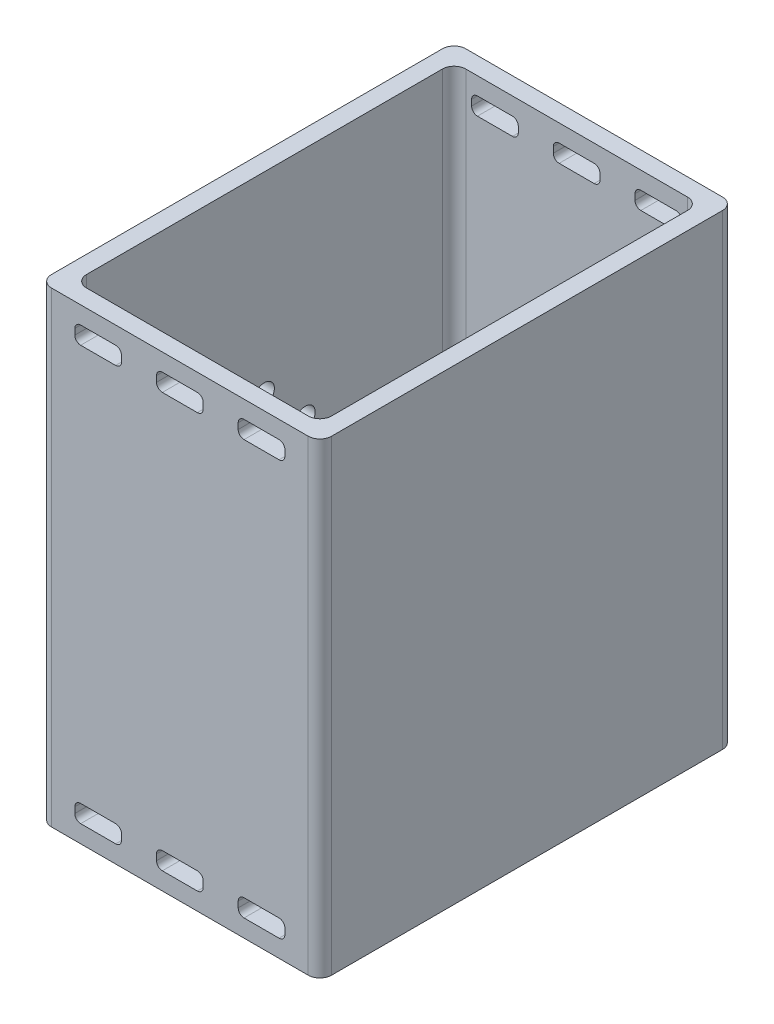
SolidWorks part; units mm, degrees
ref_plane "Front Plane" through (0, 0, 0) normal (0, 0, 1) x (1, 0, 0)
ref_plane "Top Plane" through (0, 0, 0) normal (0, 1, 0) x (1, 0, 0)
ref_plane "Right Plane" through (0, 0, 0) normal (1, 0, 0) x (0, 0, -1)
sketch "Sketch1" plane through (0, 0, 0) normal (0, 1, 0) x (1, 0, 0)
  line L0 (-24, 35.5) -> (24, 35.5)
  line L1 (-21, -32.5) -> (21, -32.5)
  line L2 (-21, -32.5) -> (-21, 32.5)
  line L3 (-21, 32.5) -> (21, 32.5)
  line L4 (21, -32.5) -> (21, 32.5)
  line L5 (-21, -32.5) -> (21, 32.5) construction
  line L6 (-21, 32.5) -> (21, -32.5) construction
  line L7 (24, -35.5) -> (24, 35.5)
  line L8 (-24, -35.5) -> (24, -35.5)
  line L9 (-24, -35.5) -> (-24, 35.5)
  point P0 (0, 0)
  dimension "D1" = 65
  dimension "D2" = 42
  dimension "D3" = 3
extrude "Boss-Extrude1" add sketch "Sketch1" along normal blind 80
sketch "Sketch2" plane through (-21, 0, 0) normal (1, 0, 0) x (0, 0, -1)
  line L0 (0, 0) -> (0, 80) construction
  line L1 (-35.5, 80) -> (35.5, 80) construction
  line L2 (-35.5, 40) -> (35.5, 40) construction
  line L3 (-35.5, 80) -> (-35.5, 0) construction
  line L4 (35.5, 80) -> (35.5, 0) construction
  circle A0 centre (0, 40) radius 1.5
  circle A1 centre (0, 40) radius 7
  circle A2 centre (-7, 40) radius 1.5
  circle A3 centre (0, 47) radius 1.5
  circle A4 centre (7, 40) radius 1.5
  circle A5 centre (0, 33) radius 1.5
  dimension "D1" = 3
  dimension "D2" = 14
  dimension "D3" = 3
  dimension "D4" = 3
  dimension "D5" = 3
  dimension "D6" = 3
hole_wizard "M3 Clearance Hole1" positions "Sketch3" profile "Sketch4" hole size "M3" standard "ISO"
sketch "Sketch3" plane through (-21, 0, 0) normal (1, 0, 0) x (0, 0, -1)
  point P0 (0, 40)
  point P3 (0, 47)
  point P6 (7, 40)
  point P9 (0, 33)
  point P12 (-7, 40)
sketch "Sketch4" plane through (-21, 40, 0) normal (0, 1, 0) x (0, 0, -1)
  line L0 (0, 0) -> (0, 3)
  line L1 (0, 3) -> (1.7, 3)
  line L2 (1.7, 3) -> (1.7, 0)
  line L5 (1.7, 0) -> (0, 0)
  line L11 (0, -6.35) -> (0, 107.95) construction
  dimension "Thru Hole Dia." = 3.4
  dimension "Thru Hole Depth" = 3
sketch "Sketch5" plane through (0, 0, 35.5) normal (0, 0, 1) x (1, 0, 0)
  line L0 (-24, 0) -> (24, 0) construction
  line L1 (-4, 6) -> (4, 6)
  line L2 (-4, 6) -> (-4, 3)
  line L3 (-4, 3) -> (4, 3)
  line L4 (4, 6) -> (4, 3)
  line L5 (-4, 6) -> (4, 3) construction
  line L6 (-4, 3) -> (4, 6) construction
  line L7 (24, 40) -> (-24, 40) construction
  line L8 (24, 80) -> (24, 0) construction
  line L9 (-24, 80) -> (-24, 0) construction
  line L10 (-4, 77) -> (4, 74) construction
  line L11 (-4, 74) -> (4, 77) construction
  line L12 (4, 74) -> (4, 77)
  line L13 (-4, 77) -> (4, 77)
  line L14 (-4, 74) -> (-4, 77)
  line L15 (-4, 74) -> (4, 74)
  line L16 (4, 4.5) -> (24, 4.5) construction
  line L17 (-4, 4.5) -> (-24, 4.5) construction
  line L18 (-18, 77) -> (-10, 74) construction
  line L19 (10, 6) -> (18, 6)
  line L20 (10, 6) -> (10, 3)
  line L21 (10, 3) -> (18, 3)
  line L22 (18, 6) -> (18, 3)
  line L23 (10, 6) -> (18, 3) construction
  line L24 (10, 3) -> (18, 6) construction
  line L25 (-18, 6) -> (-10, 6)
  line L26 (-18, 6) -> (-18, 3)
  line L27 (-18, 3) -> (-10, 3)
  line L28 (-10, 6) -> (-10, 3)
  line L29 (-18, 6) -> (-10, 3) construction
  line L30 (-18, 3) -> (-10, 6) construction
  line L31 (-18, 74) -> (-10, 77) construction
  line L32 (-4, 75.5) -> (-24, 75.5) construction
  line L33 (-10, 74) -> (-10, 77)
  line L34 (-18, 77) -> (-10, 77)
  line L35 (-18, 74) -> (-18, 77)
  line L36 (-18, 74) -> (-10, 74)
  line L37 (10, 77) -> (18, 74) construction
  line L38 (10, 74) -> (18, 77) construction
  line L39 (18, 74) -> (18, 77)
  line L40 (10, 77) -> (18, 77)
  line L41 (10, 74) -> (10, 77)
  line L42 (10, 74) -> (18, 74)
  point P0 (0, 4.5)
  point P13 (14, 4.5)
  point P25 (0, 75.5)
  point P28 (-14, 4.5)
  point P39 (-14, 75.5)
  point P44 (14, 75.5)
  dimension "D1" = 3
  dimension "D2" = 8
  dimension "D3" = 3
  dimension "D4" = 0
  dimension "D5" = 3
  dimension "D6" = 8
  dimension "D7" = 3
  dimension "D8" = 8
extrude "Cut-Extrude1" cut sketch "Sketch5" against normal through all
fillet "Fillet1" radius 2 8 edges at (-21, 40, 32.5) (-24, 40, 35.5) (-21, 40, -32.5) (-24, 40, -35.5) (21, 40, -32.5) (24, 40, -35.5) (21, 40, 32.5) (24, 40, 35.5)
fillet "Fillet2" radius 1 48 edges at (4, 6, 34) (-4, 6, 34) (4, 3, 34) (-4, 3, 34) (18, 6, 34) (10, 6, 34) (10, 3, 34) (18, 3, 34) (-10, 3, 34) (-10, 6, 34) (-18, 6, 34) (-18, 3, 34) (-18, 74, 34) (-10, 74, 34) (-10, 77, 34) (-18, 77, 34) (-4, 77, 34) (4, 77, 34) (4, 74, 34) (-4, 74, 34) (10, 74, 34) (10, 77, 34) (18, 74, 34) (18, 77, 34) (10, 74, -34) (10, 77, -34) (18, 77, -34) (18, 74, -34) (-4, 74, -34) (-4, 77, -34) (4, 74, -34) (4, 77, -34) (-10, 77, -34) (-10, 74, -34) (-18, 74, -34) (-18, 77, -34) (-18, 3, -34) (-10, 6, -34) (-10, 3, -34) (-18, 6, -34) (-4, 3, -34) (-4, 6, -34) (4, 3, -34) (4, 6, -34) (10, 3, -34) (10, 6, -34) (18, 6, -34) (18, 3, -34)
